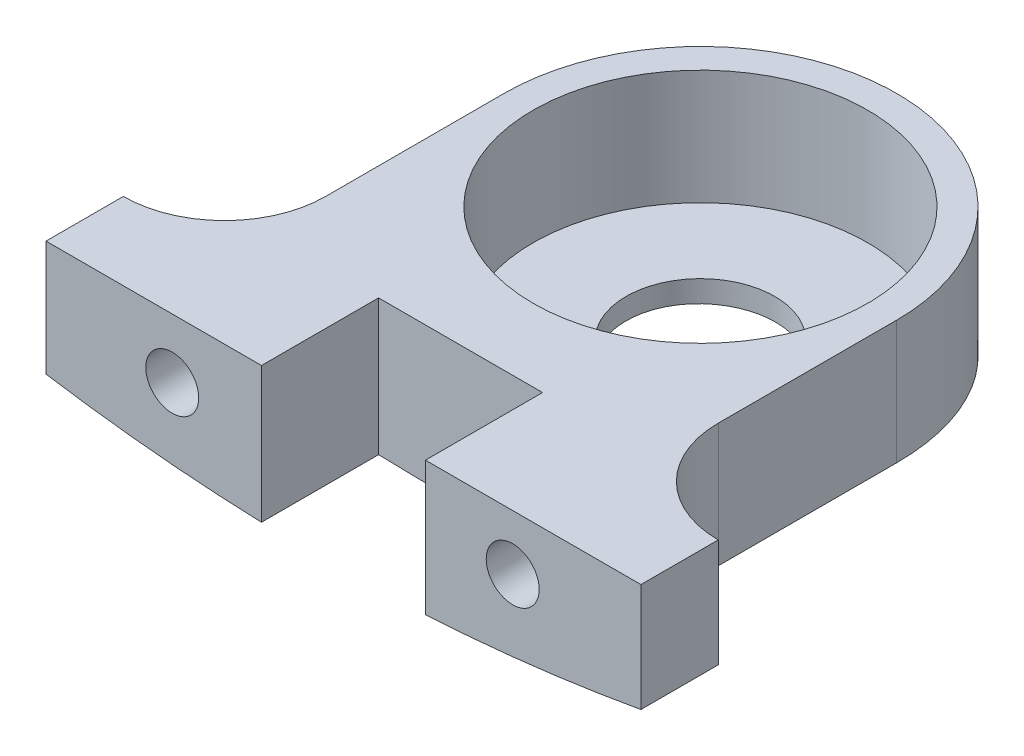
SolidWorks part; units mm, degrees
ref_plane "Front Plane" through (0, 0, 0) normal (0, 0, 1) x (1, 0, 0)
ref_plane "Top Plane" through (0, 0, 0) normal (0, 1, 0) x (1, 0, 0)
ref_plane "Right Plane" through (0, 0, 0) normal (1, 0, 0) x (0, 0, -1)
sketch "Sketch1" plane through (0, 0, 0) normal (0, 1, 0) x (1, 0, 0)
  line L1 (0, 0) -> (25.4, 0)
  line L2 (0, 0) -> (0, 23.622)
  line L3 (0, 23.622) -> (25.4, 23.622)
  line L4 (25.4, 0) -> (25.4, 23.622)
  dimension "D1" = 23.622
  dimension "D2" = 25.4
extrude "Boss-Extrude1" add sketch "Sketch1" along normal blind 5.842
sketch "Sketch2" plane through (0, 5.842, 0) normal (0, 1, 0) x (1, 0, 0)
  line L0 (0, 0) -> (25.4, 0) construction
  line L1 (0, 23.622) -> (0, 0) construction
  circle A0 centre (12.7, 15.24) radius 3.175
  dimension "D1" = 15.24
  dimension "D3" = 6.35
  dimension "D2" = 12.7
extrude "Cut-Extrude1" cut sketch "Sketch2" against normal through all contours A0
sketch "Sketch3" plane through (0, 5.842, 0) normal (0, 1, 0) x (1, 0, 0)
  line L0 (0, 0) -> (25.4, 0) construction
  line L1 (0, 23.622) -> (0, 0) construction
  circle A0 centre (12.7, 15.24) radius 7.1438
  dimension "D1" = 15.24
  dimension "D3" = 14.2875
  dimension "D2" = 12.7
extrude "Cut-Extrude2" cut sketch "Sketch3" against normal blind 4.9022
sketch "Sketch4" plane through (0, 5.842, 0) normal (0, 1, 0) x (1, 0, 0)
  line L1 (21.082, 15.24) -> (21.082, 7.62)
  line L3 (4.318, 15.24) -> (4.318, 7.62)
  line L4 (25.4, 0) -> (25.4, 23.622) construction
  line L5 (0, 23.622) -> (0, 0) construction
  line L6 (0, 3.302) -> (0, 23.622)
  line L7 (0, 23.622) -> (25.4, 23.622)
  line L8 (25.4, 23.622) -> (25.4, 3.302)
  arc A0 (21.082, 15.24) -> (4.318, 15.24) centre (12.7, 15.24) ccw
  arc A1 (21.082, 7.62) -> (25.4, 3.302) centre (25.4, 7.62) ccw
  arc A2 (0, 3.302) -> (4.318, 7.62) centre (0, 7.62) ccw
  line M2 (0, 23.622) -> (0, 0)
  line M4 (25.4, 0) -> (25.4, 23.622)
  line M5 (25.4, 23.622) -> (0, 23.622)
extrude "Cut-Extrude3" cut sketch "Sketch4" against normal through all contours A2 L3 A0 L7 M2 | L1 A1 A0 M4 M5
sketch "Sketch5" plane through (0, 0, 0) normal (0, 0, 1) x (1, 0, 0)
  line L1 (0, 0) -> (25.4, 0)
  line L2 (0, 5.842) -> (0, 0) construction
  line L3 (0, 0) -> (0, 0.9209)
  line L4 (25.4, 0) -> (25.4, 1.2215)
  line L5 (25.4, 5.842) -> (25.4, 0) construction
  arc A0 (0, 0.9209) -> (25.4, 1.2215) centre (11.811, 76.2) ccw
  line M2 (0, 0) -> (25.4, 0)
  line M3 (25.4, 0) -> (25.4, 5.842)
  line M5 (0, 5.842) -> (0, 0)
  dimension "D1" = 152.4
  dimension "D2" = 11.811
extrude "Cut-Extrude4" cut sketch "Sketch5" against normal through all contours A0 M5 M2 | A0 L1 M3
sketch "Sketch6" plane through (0, 5.842, 0) normal (0, 1, 0) x (1, 0, 0)
  line L0 (0, 0) -> (25.4, 0) construction
  line L1 (9.2, 0) -> (16.2, 0)
  line L2 (9.2, 0) -> (9.2, 5)
  line L3 (9.2, 5) -> (16.2, 5)
  line L4 (16.2, 0) -> (16.2, 5)
  line L5 (0, 3.302) -> (0, 0) construction
  dimension "D1" = 5
  dimension "D2" = 7
  dimension "D3" = 9.2
extrude "Cut-Extrude5" cut sketch "Sketch6" against normal through all
sketch "Sketch8" plane through (0, 0, 0) normal (0, 0, 1) x (1, 0, 0)
  line L0 (0, 5.842) -> (9.2, 5.842) construction
  line L1 (9.2, 0.0447) -> (9.2, 5.842) construction
  line L2 (16.2, 0.1265) -> (16.2, 5.842) construction
  line L3 (12.7, 0.0934) -> (12.6486, 4.13) construction
  line L5 (16.2, 5.842) -> (25.4, 5.842) construction
  circle A0 centre (5.39, 3.302) radius 1.1303
  circle A1 centre (19.9259, 3.4872) radius 1.1303
  dimension "D1" = 2.2606
  dimension "D2" = 2.54
  dimension "D3" = 3.81
  dimension "D4" = 3.7259
  dimension "D5" = 2.3548
extrude "Cut-Extrude6" cut sketch "Sketch8" against normal blind 6.35
